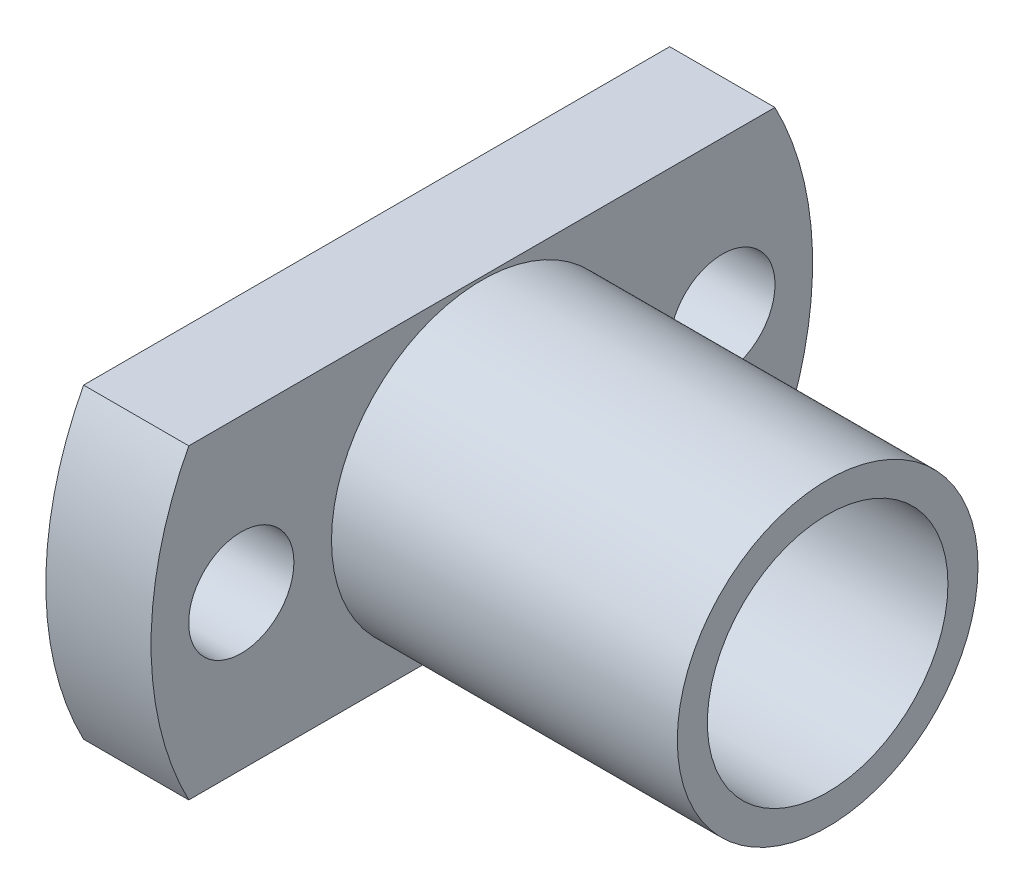
SolidWorks part; units mm, degrees
ref_plane "前视基准面" through (0, 0, 0) normal (0, 0, 1) x (1, 0, 0)
ref_plane "上视基准面" through (0, 0, 0) normal (0, 1, 0) x (1, 0, 0)
ref_plane "右视基准面" through (0, 0, 0) normal (1, 0, 0) x (0, 0, -1)
sketch "草图1" plane through (0, 0, 0) normal (1, 0, 0) x (0, 0, -1)
  circle A0 centre (0, 0) radius 5
  circle A1 centre (0, 0) radius 4
extrude "凸台-拉伸1" add sketch "草图1" along normal blind 1.5
sketch "草图2" plane through (1.5, 0, 0) normal (1, 0, 0) x (0, 0, -1)
  line L0 (0, 0) -> (27.5866, 0) construction
  line L1 (0, 0) -> (0, 8.7846) construction
  line L2 (-9.7463, 5.1) -> (9.7463, 5.1)
  line L3 (-9.7463, -5.1) -> (9.7463, -5.1)
  circle A0 centre (0, 0) radius 4
  arc A1 (9.7463, -5.1) -> (9.7463, 5.1) centre (0, 0) ccw
  circle A2 centre (0, 0) radius 8 construction
  circle A3 centre (-8, 0) radius 1.75
  circle A4 centre (8, 0) radius 1.75
  arc A5 (-9.7463, 5.1) -> (-9.7463, -5.1) centre (0, 0) ccw
  point P16 (0, 0)
  dimension "D1" = 3.5
  dimension "D3" = 5.1
  dimension "D4" = 5.1
  dimension "D2" = 2
extrude "凸台-拉伸2" add sketch "草图2" along normal blind 3.5
sketch "草图3" plane through (5, 0, 0) normal (1, 0, 0) x (0, 0, -1)
  circle A0 centre (0, 0) radius 4
  circle A1 centre (0, 0) radius 5
extrude "凸台-拉伸3" add sketch "草图3" along normal blind 11.5
sketch "草图4" plane through (0, 0, 0) normal (-1, 0, 0) x (0, 0, 1)
  circle A0 centre (0, 0) radius 5
extrude "切除-拉伸1" cut sketch "草图4" against normal up to surface (1.5 mm away) up to face at (1.5, 0, -5)
